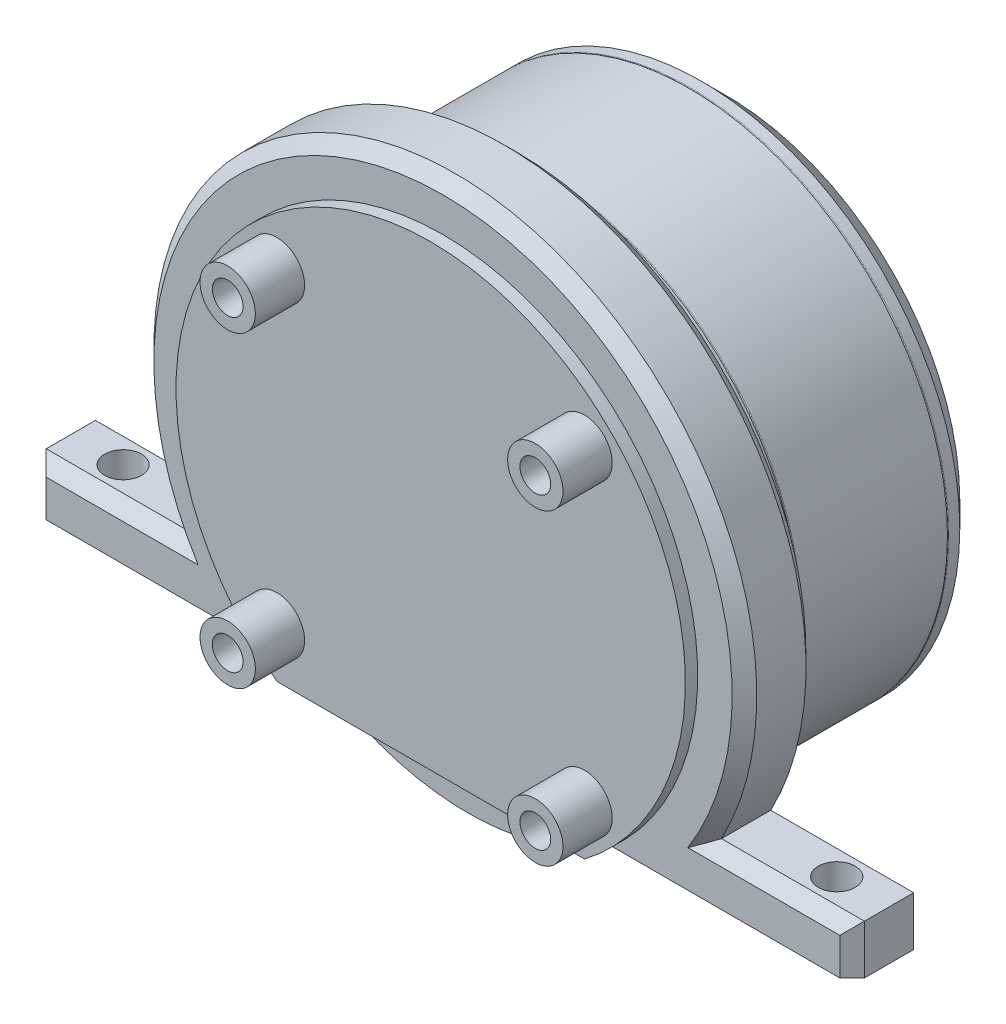
SolidWorks part; units mm, degrees
ref_plane "Front Plane" through (0, 0, 0) normal (0, 0, 1) x (1, 0, 0)
ref_plane "Top Plane" through (0, 0, 0) normal (0, 1, 0) x (1, 0, 0)
ref_plane "Right Plane" through (0, 0, 0) normal (1, 0, 0) x (0, 0, -1)
sketch "Sketch1" plane through (0, 0, 0) normal (0, 0, 1) x (1, 0, 0)
  circle A0 centre (0, 0) radius 21
  dimension "D1" = 42
extrude "Boss-Extrude1" add sketch "Sketch1" along normal blind 3
chamfer "Chamfer1" distance 2 angle 45 1 edges at (21, 0, 0)
fillet "Fillet1" radius 0.1 1 edges at (21, 0, 3)
sketch "Sketch2" plane through (0, 0, 3) normal (0, 0, 1) x (1, 0, 0)
  circle A0 centre (0, 0) radius 21 construction
  circle A1 centre (0, 0) radius 21
extrude "Boss-Extrude2" add sketch "Sketch2" along normal blind 12
fillet "Fillet2" radius 0.1 1 edges at (21, 0, 15)
sketch "Sketch3" plane through (0, 0, 15) normal (0, 0, 1) x (1, 0, 0)
  circle A0 centre (0, 0) radius 21 construction
  circle A1 centre (0, 0) radius 21
extrude "Boss-Extrude3" add sketch "Sketch3" along normal blind 6
sketch "Sketch4" plane through (0, 0, 0) normal (0, 0, -1) x (-1, 0, 0)
  line L0 (-10, 0) -> (0, 0) construction
  circle A0 centre (0, 0) radius 3
  circle A1 centre (-10, 0) radius 1.5
  circle A2 centre (0, 0) radius 3
  circle A3 centre (0, 10) radius 1.5
  circle A4 centre (0, 0) radius 3
  circle A5 centre (10, 0) radius 1.5
  circle A6 centre (0, 0) radius 3
  circle A7 centre (0, -10) radius 1.5
  point P17 (0, 0)
  dimension "D1" = 6
  dimension "D2" = 3
  dimension "D3" = 10
  dimension "D4" = 4
extrude "Cut-Extrude1" cut sketch "Sketch4" against normal blind 6
ref_plane "Plane1" through (0, 0, 17) normal (0, 0, 1) x (1, 0, 0)
sketch "Sketch5" plane through (0, 0, 17) normal (0, 0, 1) x (1, 0, 0)
  line L0 (21.6333, -11.5) -> (33.25, -11.5)
  line L1 (-33.25, -15.5) -> (33.25, -15.5)
  line L2 (-33.25, -15.5) -> (-33.25, -11.5)
  line L3 (-33.25, -11.5) -> (-21.6333, -11.5)
  line L4 (33.25, -15.5) -> (33.25, -11.5)
  line L5 (0, 0) -> (0, -15.5) construction
  arc A0 (21.6333, -11.5) -> (-21.6333, -11.5) centre (0, 0) ccw
  dimension "D1" = 49
  dimension "D2" = 66.5
  dimension "D3" = 4
  dimension "D4" = 15.5
extrude "Boss-Extrude4" add sketch "Sketch5" along normal blind 6
chamfer "Chamfer2" distance 1 angle 45 10 edges at (0, 24.5, 17) (0, 24.5, 23) (-33.25, -13.5, 17) (-27.4417, -11.5, 17) (33.25, -13.5, 17) (27.4417, -11.5, 17) (-33.25, -13.5, 23) (-27.4417, -11.5, 23) (33.25, -13.5, 23) (27.4417, -11.5, 23)
sketch "Sketch6" plane through (0, -11.5, 0) normal (0, 1, 0) x (1, 0, 0)
  line L0 (-29, -20) -> (29, -20) construction
  line L1 (0, -20) -> (0, 0) construction
  line L2 (19, 0) -> (-19, 0) construction
  line L3 (-23.5, -23) -> (23.5, -23) construction
  circle A0 centre (-29, -20) radius 1.5
  circle A1 centre (29, -20) radius 1.5
  dimension "D3" = 3
  dimension "D1" = 3
  dimension "D2" = 58
extrude "Cut-Extrude2" cut sketch "Sketch6" against normal through all and the other way through all
sketch "Sketch7" plane through (0, 0, 23) normal (0, 0, 1) x (1, 0, 0)
  line L0 (12.4996, -16.5) -> (-12.4996, -16.5)
  line L1 (-32.25, -15.5) -> (32.25, -15.5) construction
  arc A0 (12.4996, -16.5) -> (-12.4996, -16.5) centre (0, 0) ccw
  dimension "D2" = 20.7
  dimension "D1" = 1
extrude "Boss-Extrude5" add sketch "Sketch7" along normal blind 1
sketch "Sketch8" plane through (0, 0, 24) normal (0, 0, 1) x (1, 0, 0)
  line L1 (-12.5, 12.5) -> (12.5, 12.5) construction
  line L2 (-12.5, 12.5) -> (-12.5, -12.5) construction
  line L3 (-12.5, -12.5) -> (12.5, -12.5) construction
  line L4 (12.5, 12.5) -> (12.5, -12.5) construction
  line L5 (-12.5, 12.5) -> (12.5, -12.5) construction
  line L6 (-12.5, -12.5) -> (12.5, 12.5) construction
  circle A0 centre (-12.5, 12.5) radius 2.25
  circle A1 centre (12.5, 12.5) radius 2.25
  circle A2 centre (12.5, -12.5) radius 2.25
  circle A3 centre (-12.5, -12.5) radius 2.25
  point P0 (0, 0)
  dimension "D2" = 4.5
  dimension "D1" = 25
extrude "Boss-Extrude6" add sketch "Sketch8" along normal blind 4
sketch "Sketch9" plane through (0, 0, 28) normal (0, 0, 1) x (1, 0, 0)
  circle A2 centre (12.5, 12.5) radius 1.25
  circle A3 centre (12.5, 12.5) radius 1.25
  circle A4 centre (12.5, -12.5) radius 1.25
  circle A5 centre (12.5, -12.5) radius 1.25
  circle A8 centre (-12.5, 12.5) radius 1.25
  circle A9 centre (-12.5, 12.5) radius 1.25
  circle A11 centre (-12.5, -12.5) radius 1.25
  circle A12 centre (-12.5, -12.5) radius 1.25
  dimension "D1" = 1
  dimension "D2" = 1
  dimension "D3" = 1
  dimension "D4" = 1
extrude "Cut-Extrude3" cut sketch "Sketch9" against normal blind 4
